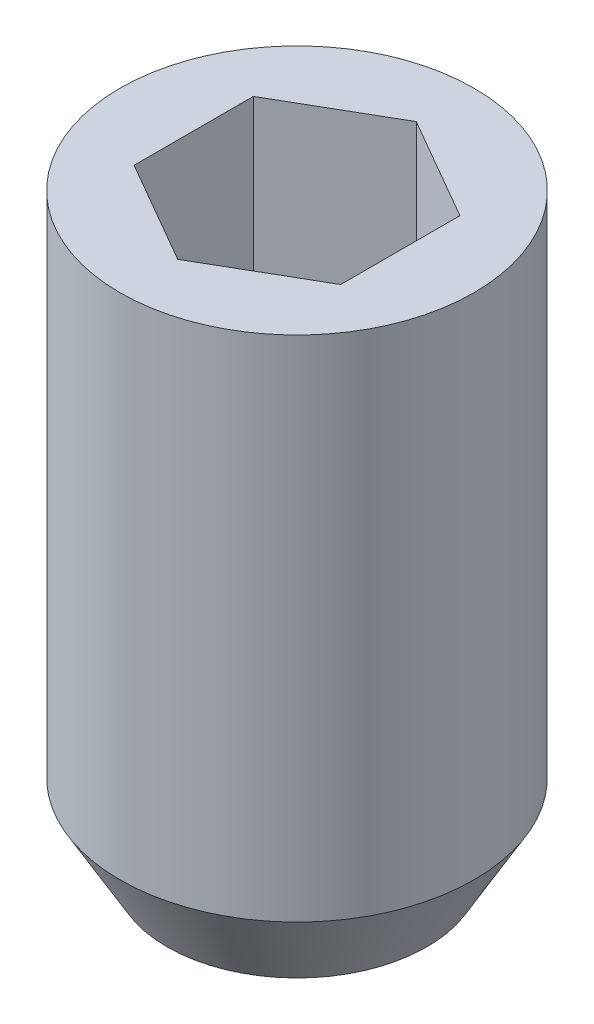
SolidWorks part; units mm, degrees
material "Plain Carbon Steel"
ref_plane "Front Plane" through (0, 0, 0) normal (0, 0, 1) x (1, 0, 0)
ref_plane "Top Plane" through (0, 0, 0) normal (0, 1, 0) x (1, 0, 0)
ref_plane "Right Plane" through (0, 0, 0) normal (1, 0, 0) x (0, 0, -1)
sketch "Sketch1" plane through (0, 0, 0) normal (0, 1, 0) x (1, 0, 0)
  circle A0 centre (0, 0) radius 1.5
  dimension "D1" = 3
extrude "Boss-Extrude1" add sketch "Sketch1" along normal blind 5
chamfer "Chamfer1" distance 0.4 angle 60 1 edges at (0, 0, 1.5)
sketch "Sketch2" plane through (0, 5, 0) normal (0, 1, 0) x (1, 0, 0)
  line L0 (0, -1.65) -> (0, 1.65) construction
  line L1 (0.875, -0.5052) -> (0.875, 0.5052)
  line L2 (0.875, 0.5052) -> (0, 1.0104)
  line L3 (0, 1.0104) -> (-0.875, 0.5052)
  line L4 (-0.875, 0.5052) -> (-0.875, -0.5052)
  line L5 (-0.875, -0.5052) -> (0, -1.0104)
  line L6 (0, -1.0104) -> (0.875, -0.5052)
  circle A0 centre (0, 0) radius 0.875 construction
  dimension "D1" = 1.75
extrude "Cut-Extrude1" cut sketch "Sketch2" against normal blind 3
